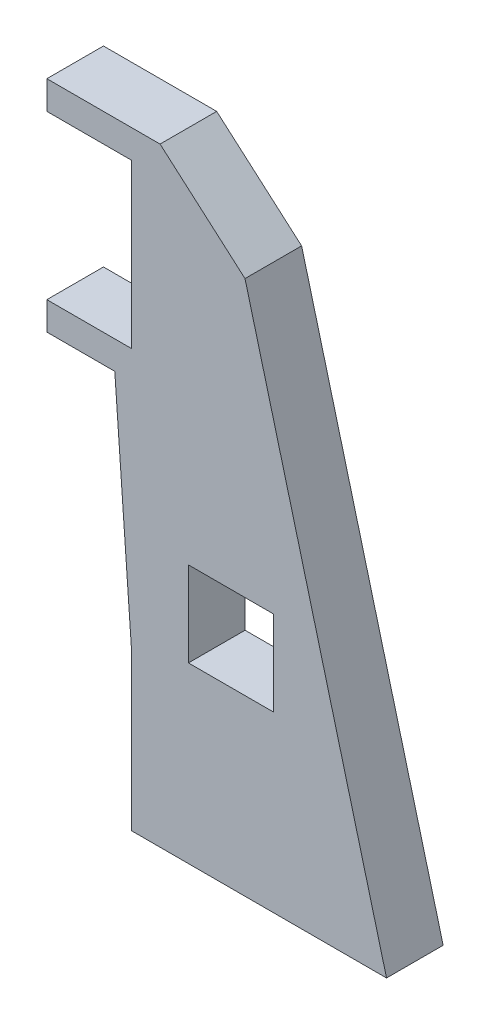
SolidWorks part; units mm, degrees
ref_plane "Front Plane" through (0, 0, 0) normal (0, 0, 1) x (1, 0, 0)
ref_plane "Top Plane" through (0, 0, 0) normal (0, 1, 0) x (1, 0, 0)
ref_plane "Right Plane" through (0, 0, 0) normal (1, 0, 0) x (0, 0, -1)
sketch "Sketch1" plane through (0, 0, 0) normal (0, 0, 1) x (1, 0, 0)
  line L0 (0, 0) -> (0, 12.7)
  line L1 (0, 12.7) -> (50.8, 12.7)
  line L2 (50.8, 12.7) -> (88.9, -20.5102)
  line L3 (0, 0) -> (38.0187, 0)
  line L4 (38.0187, 0) -> (38.0187, -73.1523)
  line L5 (38.0187, -73.1523) -> (0, -73.1523)
  line L6 (0, -73.1523) -> (0, -85.7639)
  line L7 (0, -85.7639) -> (30.48, -85.7639)
  line L10 (38.0187, -260.5159) -> (152.4, -260.5159)
  line L11 (152.4, -260.5159) -> (88.9, -20.5102)
  line L15 (30.48, -85.7639) -> (38.0187, -190.6965)
  line L16 (38.0187, -190.6965) -> (38.0187, -260.5159)
  dimension "D1" = 50.8
  dimension "D2" = 12.7
  dimension "D3" = 38.0187
  dimension "D4" = 73.1523
  dimension "D5" = 152.4
  dimension "D6" = 38.1
  dimension "D7" = 30.48
  dimension "D9" = 12.6117
  dimension "D10" = 174.752
extrude "Boss-Extrude1" add sketch "Sketch1" along normal blind 25.4
sketch "Sketch2" plane through (0, 0, 0) normal (0, 0, -1) x (-1, 0, 0)
  line L0 (0, -85.7639) -> (-30.48, -85.7639) construction
  line L1 (-63.5246, -182.5379) -> (-101.6246, -182.5379)
  line L2 (-63.5246, -182.5379) -> (-63.5246, -144.4379)
  line L3 (-63.5246, -144.4379) -> (-101.6246, -144.4379)
  line L4 (-101.6246, -182.5379) -> (-101.6246, -144.4379)
  line L5 (-38.0187, -190.6965) -> (-38.0187, -260.5159) construction
  dimension "D1" = 38.1
  dimension "D2" = 38.1
  dimension "D3" = 58.674
  dimension "D4" = 25.5059
extrude "Cut-Extrude1" cut sketch "Sketch2" against normal through all
